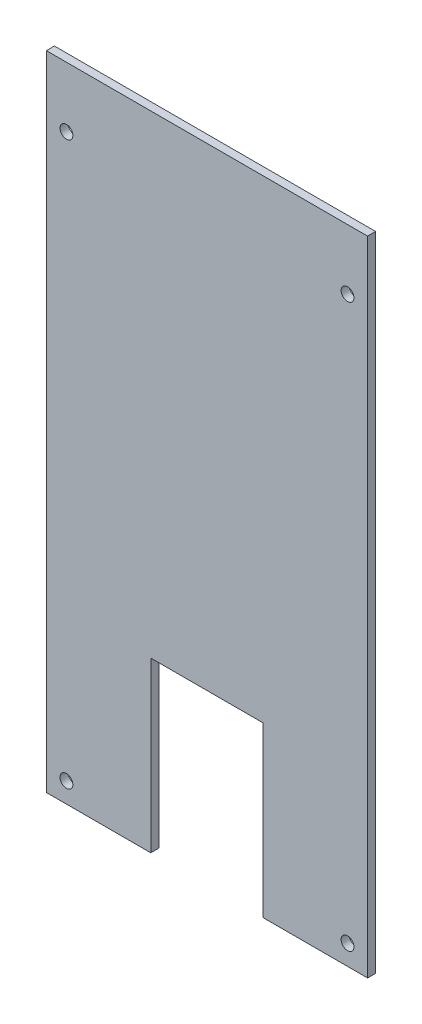
SolidWorks part; units mm, degrees
ref_plane "Plan de face" through (0, 0, 0) normal (0, 0, 1) x (1, 0, 0)
ref_plane "Plan de dessus" through (0, 0, 0) normal (0, 1, 0) x (1, 0, 0)
ref_plane "Plan de droite" through (0, 0, 0) normal (1, 0, 0) x (0, 0, -1)
sketch "Esquisse1" plane through (0, 0, 0) normal (0, 0, 1) x (1, 0, 0)
  line L0 (40, 160) -> (40, 0) construction
  line L1 (0, 0) -> (80, 0)
  line L2 (0, 0) -> (0, 160)
  line L3 (0, 160) -> (80, 160)
  line L4 (80, 0) -> (80, 160)
  line L5 (26, 42) -> (54, 42)
  line L7 (26, 42) -> (26, 0)
  line L10 (54, 42) -> (54, 0)
  point P11 (40, 42)
  dimension "D1" = 80
  dimension "D2" = 160
  dimension "D3" = 42
  dimension "D4" = 14
extrude "Boss.-Extru.1" add sketch "Esquisse1" along normal blind 2 contours L3 L0 L5 L10 L1 L4 | L0 L3 L2 L1 L7 L5
sketch "Esquisse2" plane through (0, 0, 0) normal (0, 0, 1) x (1, 0, 0)
  line L0 (5, 160) -> (5, 0) construction
  line L1 (0, 160) -> (80, 160) construction
  line L2 (0, 0) -> (26, 0) construction
  line L3 (0, 0) -> (0, 160) construction
  line L4 (40, 160) -> (40, 42) construction
  line L5 (26, 42) -> (54, 42) construction
  circle A0 centre (5, 145) radius 1.6
  circle A1 centre (5, 5) radius 1.6
  circle A3 centre (75, 5) radius 1.6
  circle A5 centre (75, 145) radius 1.6
  dimension "D2" = 3.2
  dimension "D1" = 5
  dimension "D3" = 15
  dimension "D4" = 5
extrude "Enlèv. mat.-Extru.1" cut sketch "Esquisse2" along normal blind 10
